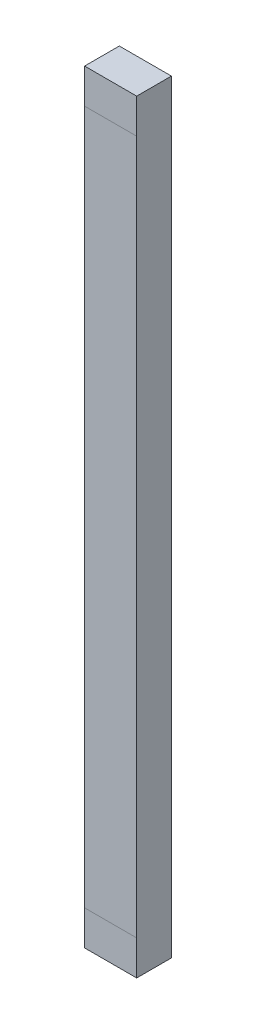
SolidWorks part; units mm, degrees
ref_plane "Płaszczyzna przednia" through (0, 0, 0) normal (0, 0, 1) x (1, 0, 0)
ref_plane "Płaszczyzna górna" through (0, 0, 0) normal (0, 1, 0) x (1, 0, 0)
ref_plane "Płaszczyzna prawa" through (0, 0, 0) normal (1, 0, 0) x (0, 0, -1)
sketch "Szkic1" plane through (0, 0, 0) normal (0, 1, 0) x (1, 0, 0)
  line L1 (0, 0) -> (150, 0)
  line L2 (0, 0) -> (0, 100)
  line L3 (0, 100) -> (150, 100)
  line L4 (150, 0) -> (150, 100)
  dimension "D1" = 150
  dimension "D2" = 100
extrude "Dodanie-wyciągnięcie1" add sketch "Szkic1" along normal blind 2200
sketch "Szkic2" plane through (0, 0, 0) normal (0, 0, 1) x (1, 0, 0)
  line L0 (0, 2100) -> (150, 2100)
  line L1 (0, 2200) -> (0, 0) construction
  line L2 (150, 2200) -> (150, 0) construction
  line L3 (0, 100) -> (150, 100)
  line L4 (0, 2200) -> (150, 2200) construction
  line L5 (0, 0) -> (150, 0) construction
  dimension "D1" = 100
  dimension "D2" = 100
split line "Linia podziałowa1"
